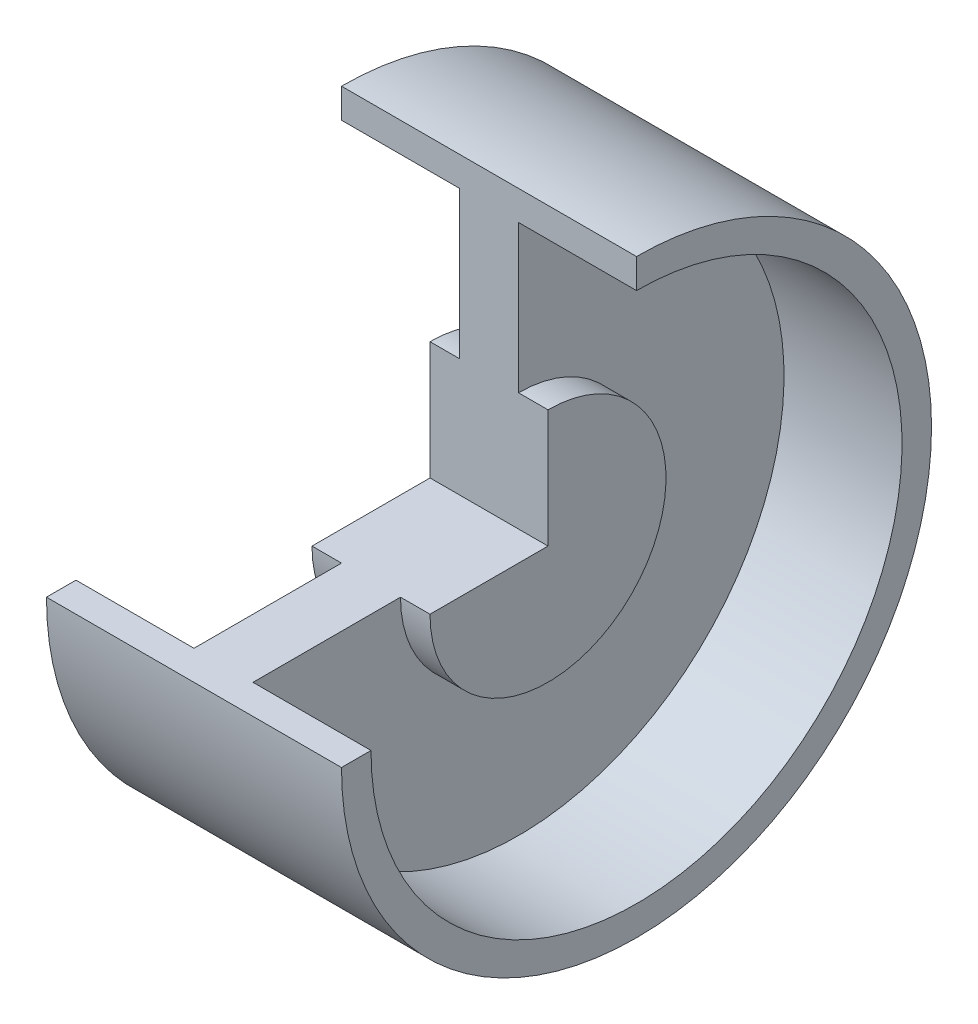
SolidWorks part; units mm, degrees
ref_plane "Front Plane" through (0, 0, 0) normal (0, 0, 1) x (1, 0, 0)
ref_plane "Top Plane" through (0, 0, 0) normal (0, 1, 0) x (1, 0, 0)
ref_plane "Right Plane" through (0, 0, 0) normal (1, 0, 0) x (0, 0, -1)
sketch "Sketch1" plane through (0, 0, 0) normal (0, 0, 1) x (1, 0, 0)
  line L0 (0, 0) -> (0, 32290.6435) construction
  line L1 (0, 0) -> (32290.6435, 0) construction
  line L2 (-10, 20) -> (-10, 0)
  line L3 (-10, 0) -> (10, 0)
  line L4 (10, 0) -> (10, 20)
  line L5 (10, 20) -> (5, 20)
  line L6 (5, 20) -> (5, 45)
  line L7 (5, 45) -> (25, 45)
  line L8 (25, 45) -> (25, 50)
  line L9 (25, 50) -> (-25, 50)
  line L10 (-25, 50) -> (-25, 45)
  line L11 (-25, 45) -> (-5, 45)
  line L12 (-5, 45) -> (-5, 20)
  line L13 (-5, 20) -> (-10, 20)
  dimension "D1" = 20
  dimension "D2" = 10
  dimension "D3" = 50
  dimension "D4" = 5
  dimension "D5" = 25
  dimension "D6" = 20
  dimension "D7" = 10
  dimension "D8" = 5
  dimension "D9" = 25
revolve "Revolve1" add sketch "Sketch1" angle 270 about L3
